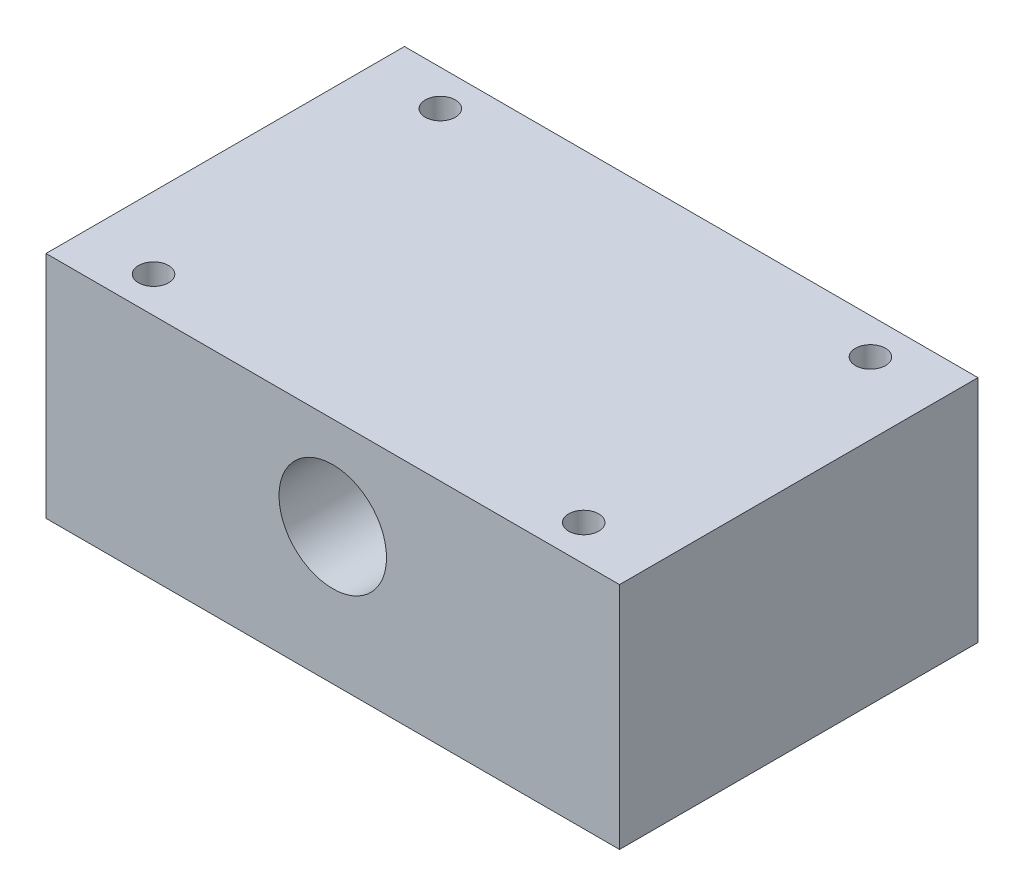
SolidWorks part; units mm, degrees
ref_plane "前视基准面" through (0, 0, 0) normal (0, 0, 1) x (1, 0, 0)
ref_plane "上视基准面" through (0, 0, 0) normal (0, 1, 0) x (1, 0, 0)
ref_plane "右视基准面" through (0, 0, 0) normal (1, 0, 0) x (0, 0, -1)
sketch "草图1" plane through (0, 0, 0) normal (0, 1, 0) x (1, 0, 0)
  line L1 (-40, -25) -> (40, -25)
  line L2 (-40, -25) -> (-40, 25)
  line L3 (-40, 25) -> (40, 25)
  line L4 (40, -25) -> (40, 25)
  line L5 (-40, -25) -> (40, 25) construction
  line L6 (-40, 25) -> (40, -25) construction
  point P0 (0, 0)
  dimension "D1" = 50
  dimension "D2" = 80
extrude "凸台-拉伸1" add sketch "草图1" along normal blind 32
sketch "草图2" plane through (0, 0, 25) normal (0, 0, 1) x (1, 0, 0)
  line L2 (-40, 0) -> (40, 0) construction
  circle A0 centre (0, 19) radius 7.5
  dimension "D1" = 15
  dimension "D2" = 19
extrude "切除-拉伸1" cut sketch "草图2" against normal through all both and the other way through all
sketch "草图3" plane through (0, 32, 0) normal (0, 1, 0) x (1, 0, 0)
  line L0 (-30, 20) -> (30, 20) construction
  line L1 (30, 20) -> (30, -20) construction
  line L2 (-35.7639, 0) -> (52.6546, 0) construction
  line L3 (-30, -20) -> (30, -20) construction
  point P6 (30, 0)
  point P7 (0, 20)
  dimension "D1" = 60
  dimension "D2" = 40
hole_wizard "M5 螺纹孔1" positions "草图4" profile "草图5" tap size "M5" standard "GB"
sketch "草图4" plane through (0, 32, 0) normal (0, 1, 0) x (1, 0, 0)
  point P0 (-30, 20)
  point P3 (30, 20)
  point P6 (30, -20)
  point P9 (-30, -20)
sketch "草图5" plane through (-30, 32, -20) normal (1, 0, 0) x (0, 0, 1)
  line L0 (0, 0) -> (0, 12.4)
  line L1 (0, 12.4) -> (2.1, 11.1382)
  line L2 (2.1, 11.1382) -> (2.1, 0)
  line L5 (2.1, 0) -> (0, 0)
  line L10 (0, 12.4) -> (-2.1, 11.1382) construction
  line L11 (0, -6.35) -> (0, 107.95) construction
  dimension "螺纹孔钻头直径" = 4.2
  dimension "螺纹孔钻头深度" = 12.4
  dimension "导头角度" = 118
cosmetic thread "孔螺蚊线1" parameters "D1"=10, "D2"=5
cosmetic thread "孔螺蚊线2" parameters "D1"=10, "D2"=5
cosmetic thread "孔螺蚊线3" parameters "D1"=10, "D2"=5
cosmetic thread "孔螺蚊线4" parameters "D1"=10, "D2"=5
sketch "草图6" plane through (-40, 0, 0) normal (-1, 0, 0) x (0, 0, 1)
  line L0 (-15, 27) -> (15, 27) construction
  line L1 (-20, 32) -> (20, 32) construction
  point P2 (0, 27)
  dimension "D1" = 5
  dimension "D2" = 30
hole_wizard "M4 螺纹孔1" positions "草图7" profile "草图8" tap size "M4" standard "GB"
sketch "草图7" plane through (-40, 0, 0) normal (-1, 0, 0) x (0, 0, 1)
  point P0 (-15, 27)
  point P3 (15, 27)
sketch "草图8" plane through (-40, 27, -15) normal (0, 1, 0) x (0, 0, 1)
  line L0 (0, 0) -> (0, 10.1)
  line L1 (0, 10.1) -> (1.65, 9.1086)
  line L2 (1.65, 9.1086) -> (1.65, 0)
  line L5 (1.65, 0) -> (0, 0)
  line L10 (0, 10.1) -> (-1.65, 9.1086) construction
  line L11 (0, -6.35) -> (0, 107.95) construction
  dimension "螺纹孔钻头直径" = 3.3
  dimension "螺纹孔钻头深度" = 10.1
  dimension "导头角度" = 118
cosmetic thread "孔螺蚊线5" parameters "D1"=8, "D2"=4
cosmetic thread "孔螺蚊线6" parameters "D1"=8, "D2"=4
